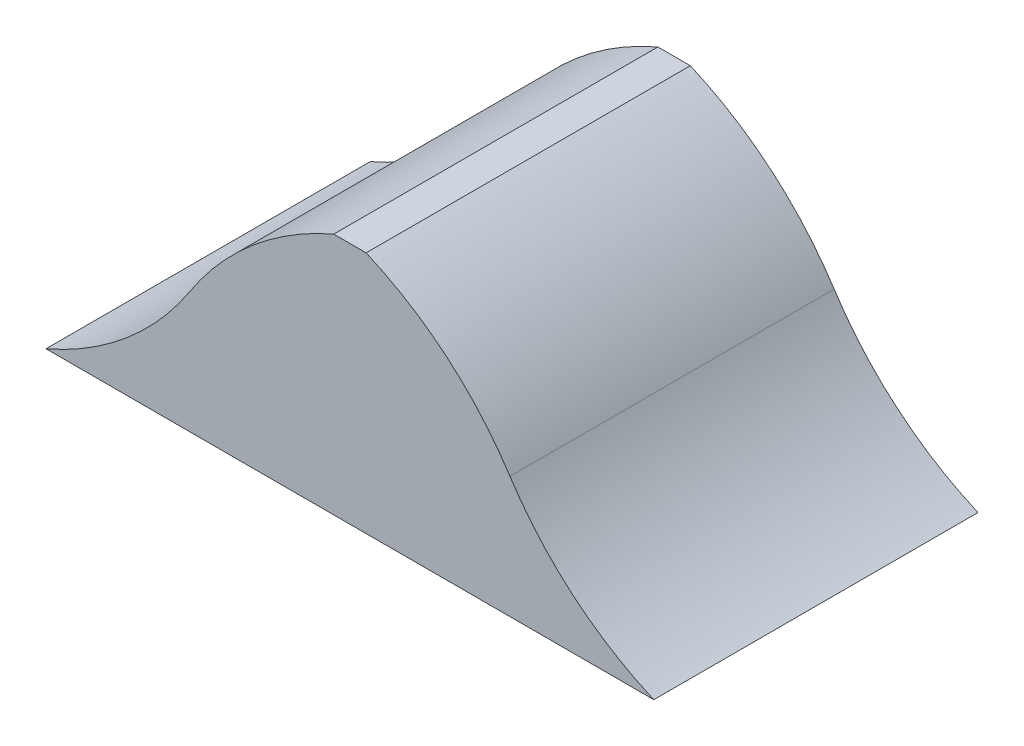
SolidWorks part; units mm, degrees
ref_plane "Front Plane" through (0, 0, 0) normal (0, 0, 1) x (1, 0, 0)
ref_plane "Top Plane" through (0, 0, 0) normal (0, 1, 0) x (1, 0, 0)
ref_plane "Right Plane" through (0, 0, 0) normal (1, 0, 0) x (0, 0, -1)
sketch "Sketch1" plane through (0, 0, 0) normal (0, 0, 1) x (1, 0, 0)
  line L0 (-375, 0) -> (375, 0)
  line L5 (-20, 300) -> (20, 300)
  arc A0 (-375, 0) -> (-197.5, 150) centre (-533.3005, 367.3431) ccw
  arc A1 (-197.5, 150) -> (-20, 300) centre (138.3005, -67.3431) cw
  arc A2 (20, 300) -> (197.5, 150) centre (-138.3005, -67.3431) cw
  arc A3 (197.5, 150) -> (375, 0) centre (533.3005, 367.3431) ccw
  point P3 (-193.8124, 43.2426)
  point P4 (0, 0)
  point P13 (1036.4384, 0)
  point P14 (689.4762, 361.8628)
  point P15 (424.9435, 790.4932)
  point P16 (-194.5063, 42.9424)
  point P17 (-164.0379, 60.1545)
  point P18 (29.3716, -290.2779)
  point P19 (36.7393, -308.3854)
  point P20 (569.6492, 349.4449)
  point P21 (-375, 392.9265)
  point P22 (605.0623, 0)
  point P23 (103.7777, -100)
  point P24 (-534.1502, 0)
  point P25 (-288.9498, 144.1876)
  point P26 (-527.0282, 0)
  point P27 (-557.551, 400)
  point P28 (-270.6361, 150)
  point P29 (0, 0)
  point P30 (-288.9498, 144.1876)
  point P31 (-443.599, 0)
  point P32 (-262.4966, 150)
  point P33 (294.0369, 136.7734)
  point P34 (424.2678, 0)
  point P35 (-298.1067, 146.575)
  point P36 (0, 0)
  point P37 (-432.4073, 0)
  point P38 (66.4251, 150)
  point P39 (-289.4998, 300)
  point P40 (94.6209, 150)
  point P41 (39.6797, 300)
  point P42 (0, 300)
  dimension "D1" = 400
  dimension "D2" = 400
  dimension "D3" = 400
  dimension "D4" = 400
  dimension "D6" = 300
  dimension "D5" = 40
  dimension "D7" = 750
  dimension "D8" = 150
  dimension "D9" = 150
extrude "Boss-Extrude1" add sketch "Sketch1" along normal blind 400
